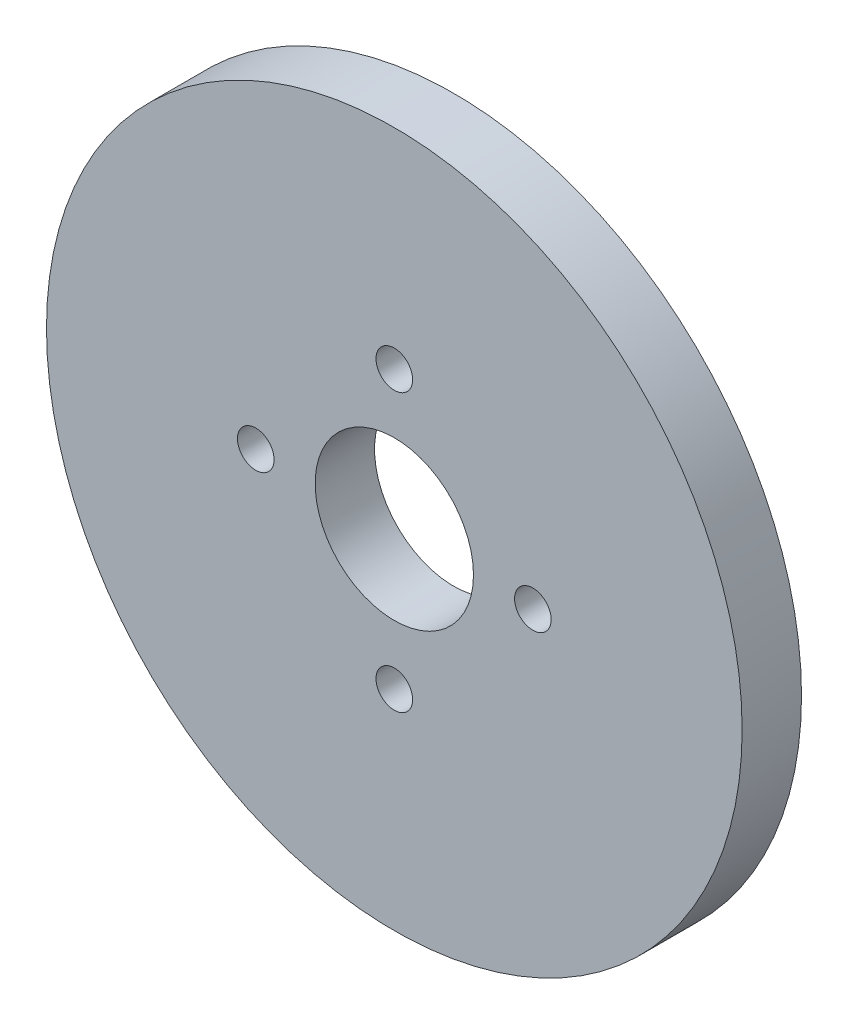
SolidWorks part; units mm, degrees
ref_plane "Plan de face" through (0, 0, 0) normal (0, 0, 1) x (1, 0, 0)
ref_plane "Plan de dessus" through (0, 0, 0) normal (0, 1, 0) x (1, 0, 0)
ref_plane "Plan de droite" through (0, 0, 0) normal (1, 0, 0) x (0, 0, -1)
sketch "Esquisse1" plane through (0, 0, 0) normal (0, 0, 1) x (1, 0, 0)
  circle A0 centre (0, 0) radius 17.575
  circle A1 centre (7, 0) radius 0.925
  circle A2 centre (0, -7) radius 0.925
  circle A3 centre (-7, 0) radius 0.925
  circle A13 centre (0, 7) radius 0.925
  circle A20 centre (0, 0) radius 4
  point P11 (0, 0)
  dimension "D1" = 8
  dimension "D2" = 1.85
  dimension "D3" = 35.15
  dimension "D4" = 7
  dimension "D5" = 4
extrude "Boss.-Extru.1" add sketch "Esquisse1" along normal blind 3
